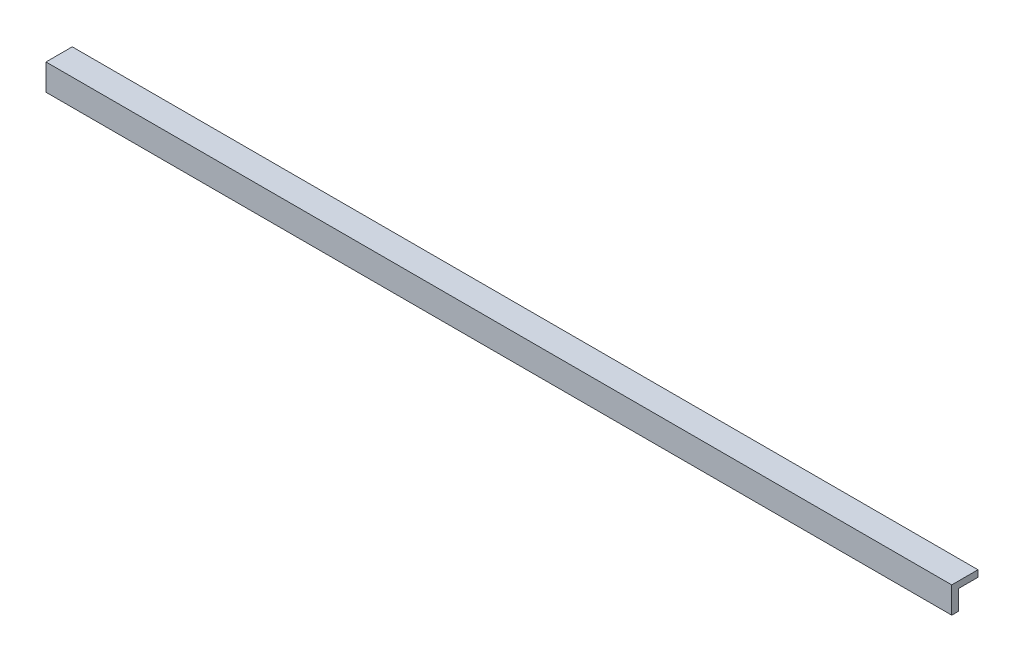
SolidWorks part; units mm, degrees
material "6061 Alloy"
ref_plane "Front Plane" through (0, 0, 0) normal (0, 0, 1) x (1, 0, 0)
ref_plane "Top Plane" through (0, 0, 0) normal (0, 1, 0) x (1, 0, 0)
ref_plane "Right Plane" through (0, 0, 0) normal (1, 0, 0) x (0, 0, -1)
sketch "Sketch1" plane through (0, 0, 0) normal (1, 0, 0) x (0, 0, -1)
  line L0 (0, 0) -> (0, 6.35)
  line L1 (0, 6.35) -> (6.35, 6.35)
  line L2 (6.35, 6.35) -> (6.35, 4.7625)
  line L3 (6.35, 4.7625) -> (1.5875, 4.7625)
  line L4 (1.5875, 4.7625) -> (1.5875, 0)
  line L5 (1.5875, 0) -> (0, 0)
  dimension "D1" = 6.35
  dimension "D2" = 6.35
  dimension "D3" = 1.5875
  dimension "D4" = 1.5875
extrude "Boss-Extrude1" add sketch "Sketch1" along normal blind 219.075
equation "\"inner_width\"= 8.625in'width between end plates"
equation "\"D1@Boss-Extrude1\"=\"inner_width\""
